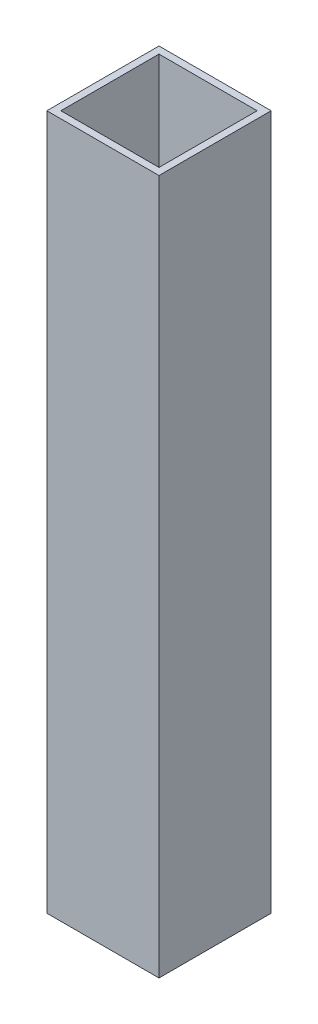
SolidWorks part; units mm, degrees
ref_plane "Front Plane" through (0, 0, 0) normal (0, 0, 1) x (1, 0, 0)
ref_plane "Top Plane" through (0, 0, 0) normal (0, 1, 0) x (1, 0, 0)
ref_plane "Right Plane" through (0, 0, 0) normal (1, 0, 0) x (0, 0, -1)
sketch "Sketch1" plane through (0, 0, 0) normal (0, 1, 0) x (1, 0, 0)
  line L1 (-25.4, -25.4) -> (25.4, -25.4)
  line L2 (-25.4, -25.4) -> (-25.4, 25.4)
  line L3 (-25.4, 25.4) -> (25.4, 25.4)
  line L4 (25.4, -25.4) -> (25.4, 25.4)
  line L5 (-25.4, -25.4) -> (25.4, 25.4) construction
  line L6 (-25.4, 25.4) -> (25.4, -25.4) construction
  line L7 (-22.225, -22.225) -> (22.225, -22.225)
  line L8 (-22.225, -22.225) -> (-22.225, 22.225)
  line L9 (-22.225, 22.225) -> (22.225, 22.225)
  line L10 (22.225, -22.225) -> (22.225, 22.225)
  point P0 (0, 0)
  dimension "D1" = 50.8
  dimension "D2" = 50.8
  dimension "D3" = 3.175
  dimension "D4" = 3.175
  dimension "D5" = 3.175
  dimension "D6" = 3.175
extrude "Boss-Extrude1" add sketch "Sketch1" along normal blind 314.8076
